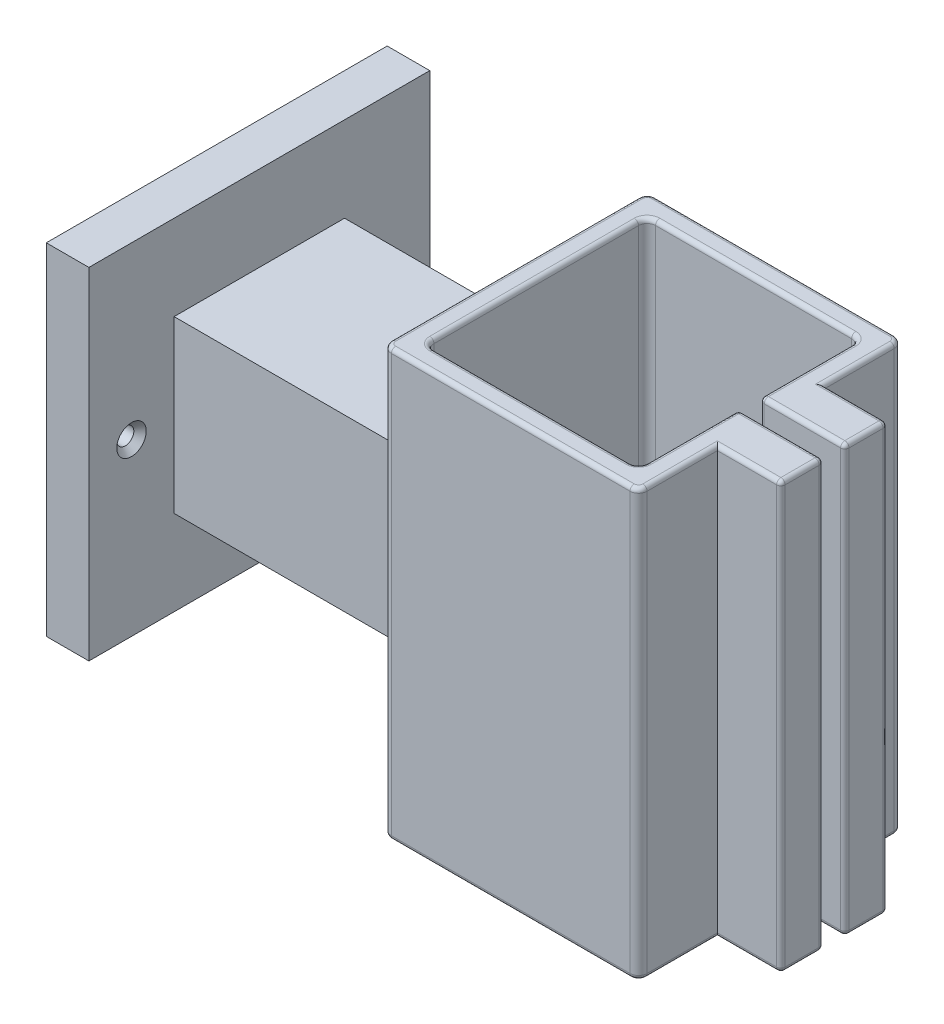
SolidWorks part; units mm, degrees
ref_plane "Front Plane" through (0, 0, 0) normal (0, 0, 1) x (1, 0, 0)
ref_plane "Top Plane" through (0, 0, 0) normal (0, 1, 0) x (1, 0, 0)
ref_plane "Right Plane" through (0, 0, 0) normal (1, 0, 0) x (0, 0, -1)
sketch "Sketch1" plane through (0, 0, 0) normal (0, 1, 0) x (1, 0, 0)
  line L0 (27.5, -1.5) -> (27.5, 27.5)
  line L1 (1, 0) -> (24, 0)
  line L2 (0, 1) -> (0, 25)
  line L3 (1, 26) -> (24, 26)
  line L4 (25, 1) -> (25, 25)
  line L5 (-1.5, 28.5) -> (26.5, 28.5)
  line L6 (-2.5, -1.5) -> (-2.5, 27.5)
  line L7 (-1.5, -2.5) -> (26.5, -2.5)
  line L8 (0, 0) -> (25, 0) construction
  line L9 (25, 0) -> (25, 26) construction
  line L10 (0, 0) -> (0, 26) construction
  line L11 (0, 26) -> (25, 26) construction
  line L12 (-2.5, -2.5) -> (-2.5, 28.5) construction
  line L13 (-2.5, -2.5) -> (27.5, -2.5) construction
  line L14 (27.5, -2.5) -> (27.5, 28.5) construction
  line L15 (-2.5, 28.5) -> (27.5, 28.5) construction
  line L16 (25, 13) -> (27.5, 13) construction
  line L18 (22.5, 14.25) -> (27.5, 14.25)
  line L19 (22.5, 14.25) -> (22.5, 11.75)
  line L20 (22.5, 11.75) -> (27.5, 11.75)
  line L21 (27.5, 14.25) -> (27.5, 11.75)
  line L22 (22.5, 14.25) -> (27.5, 11.75) construction
  line L23 (22.5, 11.75) -> (27.5, 14.25) construction
  line L24 (25, 11.75) -> (34.9522, 11.75)
  line L25 (25, 11.75) -> (25, 6.75)
  line L26 (25, 6.75) -> (34.9522, 6.75)
  line L27 (34.9522, 11.75) -> (34.9522, 6.75)
  line L28 (25, 14.25) -> (34.9522, 14.25)
  line L29 (25, 14.25) -> (25, 19.25)
  line L30 (25, 19.25) -> (34.9522, 19.25)
  line L31 (34.9522, 14.25) -> (34.9522, 19.25)
  arc A0 (24, 0) -> (25, 1) centre (24, 1) ccw
  arc A1 (1, 0) -> (0, 1) centre (1, 1) cw
  arc A2 (0, 25) -> (1, 26) centre (1, 25) cw
  arc A3 (24, 26) -> (25, 25) centre (24, 25) cw
  arc A4 (-2.5, -1.5) -> (-1.5, -2.5) centre (-1.5, -1.5) ccw
  arc A5 (27.5, -1.5) -> (26.5, -2.5) centre (26.5, -1.5) cw
  arc A6 (27.5, 27.5) -> (26.5, 28.5) centre (26.5, 27.5) ccw
  arc A7 (-1.5, 28.5) -> (-2.5, 27.5) centre (-1.5, 27.5) ccw
  point P12 (25, 0)
  dimension "D4" = 1
  dimension "D1" = 1
  dimension "D2" = 2.5
  dimension "D5" = 5
  dimension "D6" = 25
  dimension "D7" = 26
  dimension "D8" = 5
  dimension "D3" = 2.5
extrude "Boss-Extrude1" add sketch "Sketch1" along normal blind 50 contours L5 A7 L6 A4 L7 A5 L0 L20 L4 A0 L1 A1 L2 A2 L3 A3 L18 A6 | L4 L26 L0 L20 | L27 L24 L0 L26 | L28 L31 L30 L0 | L30 L4 L18 L0
sketch "Sketch5" plane through (-2.5, 0, 0) normal (-1, 0, 0) x (0, 0, 1)
  line L0 (-13, 0) -> (-13, 50) construction
  line L1 (1.5, 0) -> (-27.5, 0) construction
  line L2 (1.5, 50) -> (-27.5, 50) construction
  line L4 (-23, 15) -> (-3, 15)
  line L5 (-23, 15) -> (-23, 35)
  line L6 (-23, 35) -> (-3, 35)
  line L7 (-3, 15) -> (-3, 35)
  line L8 (-23, 15) -> (-3, 35) construction
  line L9 (-23, 35) -> (-3, 15) construction
  point P6 (-13, 25)
  dimension "D1" = 20
  dimension "D2" = 20
extrude "Boss-Extrude2" add sketch "Sketch5" along normal blind 30
sketch "Sketch6" plane through (-32.5, 0, 0) normal (-1, 0, 0) x (0, 0, 1)
  line L0 (-13, 35) -> (-13, 15) construction
  line L1 (-3, 35) -> (-23, 35) construction
  line L2 (-23, 15) -> (-3, 15) construction
  line L4 (-33, 45) -> (7, 45)
  line L5 (-33, 45) -> (-33, 5)
  line L6 (-33, 5) -> (7, 5)
  line L7 (7, 45) -> (7, 5)
  line L8 (-33, 45) -> (7, 5) construction
  line L9 (-33, 5) -> (7, 45) construction
  point P6 (-13, 25)
  dimension "D1" = 40
  dimension "D2" = 40
extrude "Boss-Extrude3" add sketch "Sketch6" along normal blind 5
sketch "Sketch10" plane through (-2.5, 0, 0) normal (-1, 0, 0) x (0, 0, 1)
  line L8 (-25.5, 2) -> (-0.5, 2)
  line L9 (-0.5, 2) -> (-0.5, 48)
  line L10 (-0.5, 48) -> (-25.5, 48)
  line L11 (-25.5, 48) -> (-25.5, 2)
  line L12 (-25.5, 2) -> (-0.5, 2)
  line L13 (-0.5, 2) -> (-0.5, 48)
  line L14 (-0.5, 48) -> (-25.5, 48)
  line L15 (-25.5, 48) -> (-25.5, 2)
  dimension "D1" = 2
sketch "Sketch7" plane through (-37.5, 0, 0) normal (-1, 0, 0) x (0, 0, 1)
  line L0 (-13, 45) -> (-13, 5) construction
  line L1 (7, 45) -> (-33, 45) construction
  line L2 (-33, 5) -> (7, 5) construction
  line L4 (-28, 37.5) -> (2, 37.5)
  line L5 (-28, 37.5) -> (-28, 12.5)
  line L6 (-28, 12.5) -> (2, 12.5)
  line L7 (2, 37.5) -> (2, 12.5)
  line L8 (-28, 37.5) -> (2, 12.5) construction
  line L9 (-28, 12.5) -> (2, 37.5) construction
  point P6 (-13, 25)
  point P11 (-28, 25)
  point P12 (2, 25)
  point P13 (21.9625, 14.4831)
  dimension "D1" = 30
  dimension "D2" = 25
sketch "Sketch8" plane through (-32.5, 0, 0) normal (1, 0, 0) x (0, 0, -1)
  point P0 (-2, 25)
  point P3 (28, 25)
hole_wizard "#2-64 Tapped Hole1" positions "Sketch8" profile "Sketch9" tap size "#2-64" standard "ANSI Inch"
sketch "Sketch9" plane through (-32.5, 25, 2) normal (0, 1, 0) x (0, 0, -1)
  line L0 (0, 0) -> (0, 5.6009)
  line L1 (0, 5.6009) -> (1, 5)
  line L2 (1, 5) -> (1, 0.7272)
  line L3 (1, 0.7272) -> (1.7272, 0)
  line L5 (1.7272, 0) -> (0, 0)
  line L6 (-1, 0.7272) -> (-1.7272, 0) construction
  line L10 (0, 5.6009) -> (-1, 5) construction
  line L11 (0, -6.35) -> (0, 107.95) construction
  dimension "Tap Drill Dia." = 2
  dimension "Tap Drill Depth" = 5
  dimension "Near C'Sink Dia." = 3.4544
  dimension "Near C'Sink Angle" = 90
  dimension "Drill Angle" = 118
cosmetic thread "Hole Thread1" parameters "D1"=3, "D2"=2.1844
cosmetic thread "Hole Thread2" parameters "D1"=3, "D2"=2.1844
fillet "Fillet2" radius 0.5 54 edges at (12.5, 0, 0) (12.5, 50, 0) (0.2929, 0, -0.2929) (0.2929, 50, -0.2929) (0, 0, -13) (0, 50, -13) (0.2929, 0, -25.7071) (0.2929, 50, -25.7071) (12.5, 0, -26) (12.5, 50, -26) (24.7071, 0, -25.7071) (24.7071, 50, -25.7071) (25, 0, -19.625) (25, 50, -19.625) (29.9761, 0, -14.25) (29.9761, 50, -14.25) (34.9522, 0, -16.75) (34.9522, 50, -16.75) (31.2261, 0, -19.25) (31.2261, 50, -19.25) (27.5, 0, -23.375) (27.5, 50, -23.375) (27.2071, 0, -28.2071) (27.2071, 50, -28.2071) (12.5, 0, -28.5) (12.5, 50, -28.5) (-2.2071, 0, -28.2071) (-2.2071, 50, -28.2071) (-2.5, 0, -13) (-2.5, 50, -13) (-2.2071, 0, 2.2071) (-2.2071, 50, 2.2071) (12.5, 0, 2.5) (12.5, 50, 2.5) (27.2071, 0, 2.2071) (27.2071, 50, 2.2071) (27.5, 0, -2.625) (27.5, 50, -2.625) (31.2261, 0, -6.75) (31.2261, 50, -6.75) (34.9522, 0, -9.25) (34.9522, 50, -9.25) (29.9761, 0, -11.75) (29.9761, 50, -11.75) (25, 0, -6.375) (25, 50, -6.375) (24.7071, 0, -0.2929) (24.7071, 50, -0.2929) (34.9522, 25, -6.75) (34.9522, 25, -11.75) (34.9522, 25, -14.25) (34.9522, 25, -19.25) (25, 25, -14.25) (25, 25, -11.75)
sketch "Sketch12" plane through (0, 0, -19.25) normal (0, 0, -1) x (-1, 0, 0)
  line L0 (-34.4522, 25) -> (-27.5, 25) construction
  line L1 (-34.4522, 49.5) -> (-34.4522, 0.5) construction
  line L2 (-27.5, 49.5) -> (-27.5, 0.5) construction
  line L3 (-30.9761, 25) -> (-30.9761, 40) construction
  line L4 (-30.9761, 25) -> (-30.9761, 10) construction
  circle A0 centre (-30.9761, 40) radius 2.5
  circle A1 centre (-30.9761, 25) radius 2.5
  circle A2 centre (-30.9761, 10) radius 2.5
  dimension "D3" = 5
  dimension "D4" = 5
  dimension "D5" = 5
  dimension "D1" = 15
  dimension "D2" = 15
extrude "Cut-Extrude1" cut sketch "Sketch12" against normal blind 1
sketch "Sketch13" plane through (0, 0, -18.25) normal (0, 0, -1) x (-1, 0, 0)
  point P0 (-30.9761, 40)
  point P1 (-30.9761, 25)
  point P3 (-30.9761, 10)
sketch "Sketch14" plane through (0, 0, -18.25) normal (0, 0, -1) x (-1, 0, 0)
  point P0 (-30.9761, 40)
  point P3 (-30.9761, 25)
  point P6 (-30.9761, 10)
hole_wizard "#4-40 Tapped Hole1" positions "Sketch14" profile "Sketch15" tap size "#4-40" standard "ANSI Inch"
sketch "Sketch15" plane through (30.9761, 40, -18.25) normal (1, 0, 0) x (0, 1, 0)
  line L0 (0, 0) -> (0, 11)
  line L1 (0, 11) -> (1.1303, 10.3208)
  line L2 (1.1303, 10.3208) -> (1.1303, 0.9271)
  line L3 (1.1303, 0.9271) -> (2.0574, 0)
  line L5 (2.0574, 0) -> (0, 0)
  line L6 (-1.1303, 0.9271) -> (-2.0574, 0) construction
  line L10 (0, 11) -> (-1.1303, 10.3208) construction
  line L11 (0, -6.35) -> (0, 107.95) construction
  dimension "Tap Drill Dia." = 2.2606
  dimension "Tap Drill Depth" = 11
  dimension "Near C'Sink Dia." = 4.1148
  dimension "Near C'Sink Angle" = 90
  dimension "Drill Angle" = 118
cosmetic thread "Hole Thread3" parameters "D1"=10, "D2"=2.8448
cosmetic thread "Hole Thread4" parameters "D1"=10, "D2"=2.8448
cosmetic thread "Hole Thread5" parameters "D1"=10, "D2"=2.8448
equation "\"25mnm\"=44.5714"
equation "\"50mmmm\"=10"
